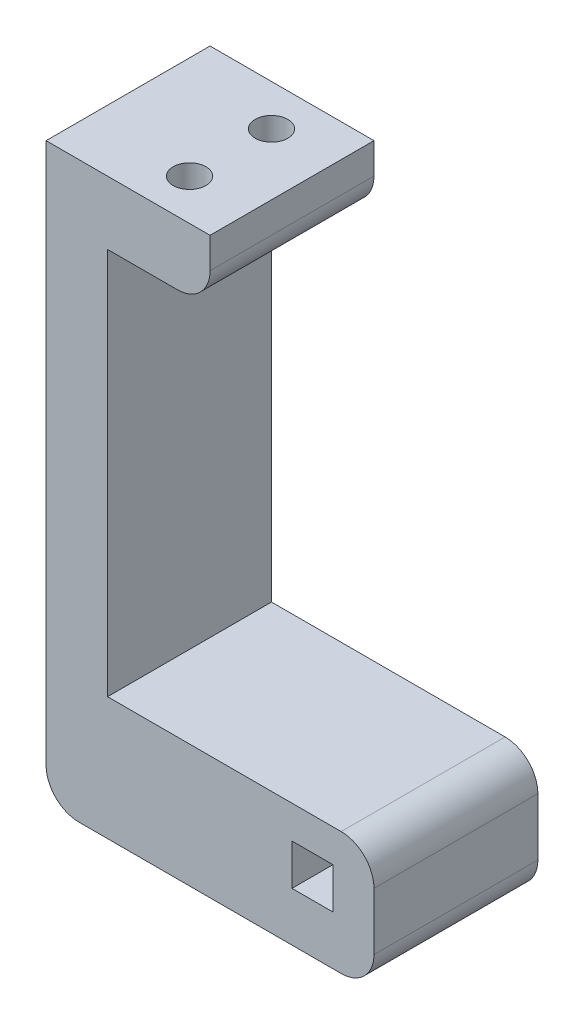
SolidWorks part; units mm, degrees
ref_plane "Front Plane" through (0, 0, 0) normal (0, 0, 1) x (1, 0, 0)
ref_plane "Top Plane" through (0, 0, 0) normal (0, 1, 0) x (1, 0, 0)
ref_plane "Right Plane" through (0, 0, 0) normal (1, 0, 0) x (0, 0, -1)
sketch "Sketch1" plane through (0, 0, 0) normal (0, 0, 1) x (1, 0, 0)
  line L0 (10.16, 0) -> (91.44, 0)
  line L1 (101.6, 10.16) -> (101.6, 27.94)
  line L2 (91.44, 38.1) -> (19.05, 38.1)
  line L3 (19.05, 38.1) -> (19.05, 158.1298)
  line L4 (19.05, 158.1298) -> (40.64, 158.1298)
  line L5 (50.8, 168.2898) -> (50.8, 177.8)
  line L6 (50.8, 177.8) -> (0, 177.8)
  line L7 (0, 177.8) -> (0, 10.16)
  arc A0 (40.64, 158.1298) -> (50.8, 168.2898) centre (40.64, 168.2898) ccw
  arc A1 (10.16, 0) -> (0, 10.16) centre (10.16, 10.16) cw
  arc A2 (91.44, 0) -> (101.6, 10.16) centre (91.44, 10.16) ccw
  arc A3 (101.6, 27.94) -> (91.44, 38.1) centre (91.44, 27.94) ccw
  point P11 (50.8, 158.1298)
  point P14 (0, 0)
  point P17 (101.6, 0)
  point P20 (101.6, 38.1)
  dimension "D6" = 10.16
  dimension "D1" = 101.6
  dimension "D2" = 38.1
  dimension "D3" = 177.8
  dimension "D4" = 50.8
  dimension "D5" = 31.75
  dimension "D7" = 158.1298
extrude "Boss-Extrude1" add sketch "Sketch1" along normal mid plane 50.8
sketch "Sketch2" plane through (0, 0, 25.4) normal (0, 0, 1) x (1, 0, 0)
  line L0 (91.44, 38.1) -> (19.05, 38.1) construction
  line L1 (76.2, 27.94) -> (88.9, 27.94)
  line L2 (76.2, 27.94) -> (76.2, 15.24)
  line L3 (76.2, 15.24) -> (88.9, 15.24)
  line L4 (88.9, 27.94) -> (88.9, 15.24)
  line L5 (76.2, 27.94) -> (88.9, 15.24) construction
  line L6 (76.2, 15.24) -> (88.9, 27.94) construction
  line L8 (101.6, 10.16) -> (101.6, 27.94) construction
  point P4 (82.55, 21.59)
  point P5 (0, 0)
  point P6 (0, 0)
  point P7 (68.3831, 30.4847)
  point P12 (101.6, 19.05)
  dimension "D1" = 12.7
  dimension "D2" = 12.7
  dimension "D3" = 10.16
  dimension "D4" = 12.7
extrude "Cut-Extrude1" cut sketch "Sketch2" against normal blind 50.8
sketch "Sketch3" plane through (0, 158.1298, 0) normal (0, -1, 0) x (1, 0, 0)
  line L0 (19.05, 25.4) -> (40.64, 25.4) construction
  line L1 (19.05, -25.4) -> (40.64, -25.4) construction
  line L2 (19.05, 25.4) -> (19.05, -25.4) construction
  circle A0 centre (31.75, 12.7) radius 5.0723
  circle A1 centre (31.75, -12.7) radius 5.0723
  point P10 (0, 0)
  point P11 (0, 0)
  dimension "D3" = 12.7
  dimension "D4" = 10.1447
  dimension "D1" = 12.7
  dimension "D2" = 12.7
extrude "Cut-Extrude2" cut sketch "Sketch3" against normal blind 50.8
